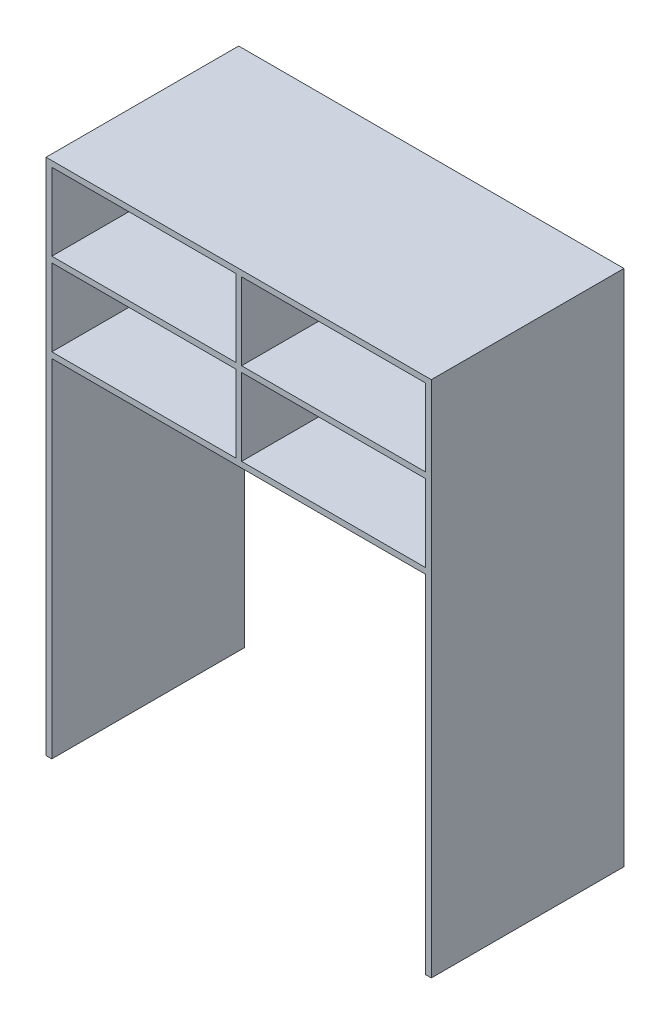
SolidWorks part; units mm, degrees
ref_plane "Front Plane" through (0, 0, 0) normal (0, 0, 1) x (1, 0, 0)
ref_plane "Top Plane" through (0, 0, 0) normal (0, 1, 0) x (1, 0, 0)
ref_plane "Right Plane" through (0, 0, 0) normal (1, 0, 0) x (0, 0, -1)
sketch "Sketch1" plane through (0, 0, 0) normal (0, 0, 1) x (1, 0, 0)
  line L0 (-97, 0) -> (97, 0)
  line L1 (97, 0) -> (97, -180)
  line L2 (97, -180) -> (100, -180)
  line L3 (100, -180) -> (100, 89)
  line L4 (100, 89) -> (-100, 89)
  line L5 (-100, 89) -> (-100, -180)
  line L6 (-100, -180) -> (-97, -180)
  line L7 (-97, -180) -> (-97, 0)
  line L8 (-97, 3) -> (-97, 43)
  line L9 (-97, 43) -> (-1.5, 43)
  line L10 (-1.5, 43) -> (-1.5, 3)
  line L11 (-1.5, 3) -> (-97, 3)
  line L12 (-97, 46) -> (-97, 86)
  line L13 (-97, 86) -> (-1.5, 86)
  line L14 (-1.5, 86) -> (-1.5, 46)
  line L15 (-1.5, 46) -> (-97, 46)
  line L16 (1.5, 46) -> (1.5, 86)
  line L17 (1.5, 86) -> (97, 86)
  line L18 (97, 86) -> (97, 46)
  line L19 (97, 46) -> (1.5, 46)
  line L20 (1.5, 43) -> (1.5, 3)
  line L21 (1.5, 3) -> (97, 3)
  line L22 (1.5, 43) -> (97, 43)
  line L23 (97, 43) -> (97, 3)
  point P18 (0, 0)
  dimension "D1" = 3
  dimension "D2" = 3
  dimension "D3" = 3
  dimension "D4" = 40
  dimension "D5" = 180
  dimension "D6" = 3
  dimension "D7" = 3
  dimension "D8" = 200
extrude "Boss-Extrude1" add sketch "Sketch1" along normal blind 100
